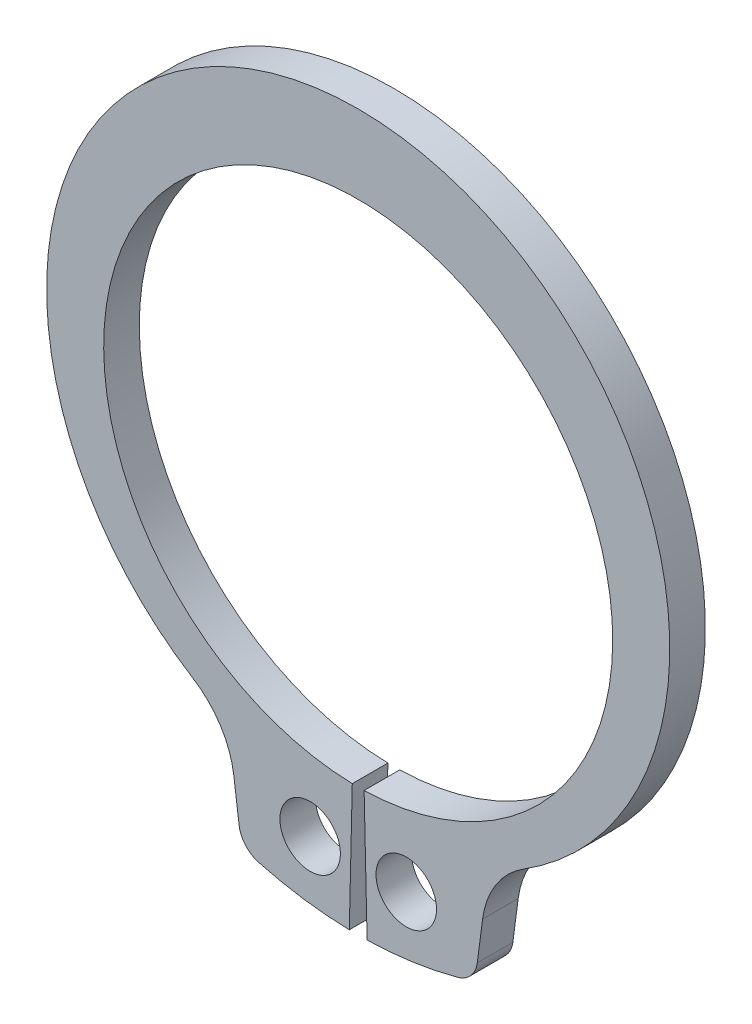
SolidWorks part; units mm, degrees
ref_plane "Plane1" through (0, 0, 0) normal (0, 0, 1) x (1, 0, 0)
ref_plane "Plane2" through (0, 0, 0) normal (0, 1, 0) x (1, 0, 0)
ref_plane "Plane3" through (0, 0, 0) normal (1, 0, 0) x (0, 0, -1)
extrude "Body" add sketch "BodySke" against normal blind 1
sketch "BodySke" plane through (0, 0, 0) normal (0, 0, 1) x (1, 0, 0)
  line L0 (-1.5431, 0) -> (1.5431, 0) construction
  line L1 (0, 0) -> (0, 9.35) construction
  line L2 (0.1663, -7.1481) -> (0.25, -10.7471)
  line L3 (-0.1663, -7.1481) -> (-0.25, -10.7471)
  line L4 (0, 0) -> (5.972, -8.9385) construction
  line L5 (0, 0) -> (-5.972, -8.9385) construction
  line L7 (3.4948, -8.6124) -> (3.3446, -9.7537)
  line L8 (-3.4948, -8.6124) -> (-3.3446, -9.7537)
  circle A0 centre (0, 0) radius 7.15 construction
  arc A1 (0.1663, -7.1481) -> (-0.1663, -7.1481) centre (0, 0) ccw
  arc A2 (4.5832, -6.8598) -> (-4.5832, -6.8598) centre (0, 0.5972) ccw construction
  arc A3 (0.25, -10.7471) -> (2.7961, -10.38) centre (0, 0) ccw
  arc A4 (4.6458, -6.8209) -> (3.4948, -8.6124) centre (5.972, -8.9385) ccw
  arc A5 (-3.4948, -8.6124) -> (-4.6458, -6.8209) centre (-5.972, -8.9385) ccw
  arc A6 (-2.7961, -10.38) -> (-0.25, -10.7471) centre (0, 0) ccw
  arc A7 (4.6458, -6.8209) -> (-4.6458, -6.8209) centre (0, 0.5972) ccw
  arc A8 (-3.5203, -8.4186) -> (3.5203, -8.4186) centre (0, 0) ccw construction
  circle A9 centre (1.35, -9.0246) radius 0.85
  circle A10 centre (-1.35, -9.0246) radius 0.85
  arc A11 (3.3446, -9.7537) -> (2.7961, -10.38) centre (2.601, -9.6558) cw
  arc A12 (-3.3446, -9.7537) -> (-2.7961, -10.38) centre (-2.601, -9.6558) ccw
  point P28 (3.2809, -10.2371)
  point P31 (-3.2809, -10.2371)
  dimension "GrooveDia" = 14.3
  dimension "D3" = 0.75
  dimension "LugRad" = 10.75
  dimension "HoleOffsetRad" = 9.125
  dimension "HoleDia" = 1.7
  dimension "D2" = 15
  dimension "LargeRad" = 9.35
  dimension "SmallRad" = 8.25
  dimension "Gap" = 0.5
  dimension "SmallAngle" = 67.496
  dimension "HoleSpacing" = 2.7
sketch "Clipboard" plane through (0, 0, 0) normal (0, 0, 1) x (1, 0, 0)
  line L0 (0, 0) -> (2.2, 0)
  line L1 (0, 0) -> (0, 1.1)
  line L2 (0, 0) -> (0, -3.6)
  circle A0 centre (0, 0) radius 0.85
  circle A1 centre (0, 0) radius 7.5
  dimension "HoleDia" = 1.7
  dimension "ShaftDia" = 15
  dimension "LargeSection" = 2.2
  dimension "SmallSection" = 1.1
  dimension "LugSection" = 3.6
sketch "NotSke" plane through (0, 0, 0) normal (0, 0, 1) x (1, 0, 0)
  line L0 (1.35, -8.1746) -> (1.35, -9.8746)
  line L1 (1.35, -9.8746) -> (-1.35, -9.8746)
  line L2 (-1.35, -9.8746) -> (-1.35, -8.1746)
  line L3 (-1.35, -8.1746) -> (1.35, -8.1746)
  circle A0 centre (1.35, -9.0246) radius 0.85 construction
  circle A1 centre (-1.35, -9.0246) radius 0.85 construction
extrude "Notch" [suppressed] cut sketch "NotSke" against normal through all
sketch "UnlSke" plane through (0, 0, 0) normal (0, 0, 1) x (1, 0, 0)
  line L0 (-2.5738, -10.4373) -> (-1.7119, -6.942)
  line L1 (2.5738, -10.4373) -> (1.7119, -6.942)
  arc A0 (1.7119, -6.942) -> (-1.7119, -6.942) centre (0, 0) ccw
  arc A1 (2.5738, -10.4373) -> (-2.5738, -10.4373) centre (0, 0) ccw
  arc A2 (0.25, -10.7471) -> (2.7961, -10.38) centre (0, 0) ccw construction
  arc A3 (0.1663, -7.1481) -> (-0.1663, -7.1481) centre (0, 0) ccw construction
  circle A4 centre (-1.35, -9.0246) radius 0.85 construction
  circle A5 centre (1.35, -9.0246) radius 0.85 construction
extrude "Unlug" [suppressed] add sketch "UnlSke" against normal through all
equation "' \"ShaftDia@Clipboard\" = 3"
equation "' \"Thickness@Body\" = 0.4"
equation "' \"GrooveDia@BodySke\" = 2.8"
equation "' \"LugSection@Clipboard\" = 1.9"
equation "' \"LargeSection@Clipboard\" = 0.8"
equation "' \"HoleDia@Clipboard\" = 1.0"
equation "' \"ShaftDia@Clipboard\" = 10"
equation "' \"Thickness@Body\" = 1.0"
equation "' \"GrooveDia@BodySke\" = 9.6"
equation "' \"LugSection@Clipboard\" = 3.3"
equation "' \"LargeSection@Clipboard\" = 1.8"
equation "' \"HoleDia@Clipboard\" = 1.5"
equation "\"SmallSection@Clipboard\" = \"LargeSection@Clipboard\" * 0.5"
equation "\"Gap@BodySke\" =  \"Thickness@Body\" / 2"
equation "\"LargeRad@BodySke\" =  \"GrooveDia@BodySke\" / 2 +  \"LargeSection@Clipboard\""
equation "\"SmallRad@BodySke\" =  \"GrooveDia@BodySke\" / 2 +  \"SmallSection@Clipboard\""
equation "\"LugRad@BodySke\" = \"GrooveDia@BodySke\" / 2 + \"LugSection@Clipboard\""
equation "\"HoleOffsetRad@BodySke\" = (  \"ShaftDia@Clipboard\" / 2 + \"LugRad@BodySke\" ) / 2"
equation "\"HoleSpacing@BodySke\" = \"Gap@BodySke\"  * 2 +  \"HoleDia@Clipboard\""
equation "\"HoleDia@BodySke\" =  \"HoleDia@Clipboard\""
equation "\"SmallAngle@BodySke\" = atn(\"HoleSpacing@BodySke\" / 2 / sqr(\"HoleOffsetRad@BodySke\"  * \"HoleOffsetRad@BodySke\" - (\"HoleSpacing@BodySke\" / 2) * (\"HoleSpacing@BodySke\" / 2) ))  * 7 *  (\"LargeRad@BodySke\" / \"SmallRad@BodySke\")* ( 180 / 3.141593)"
